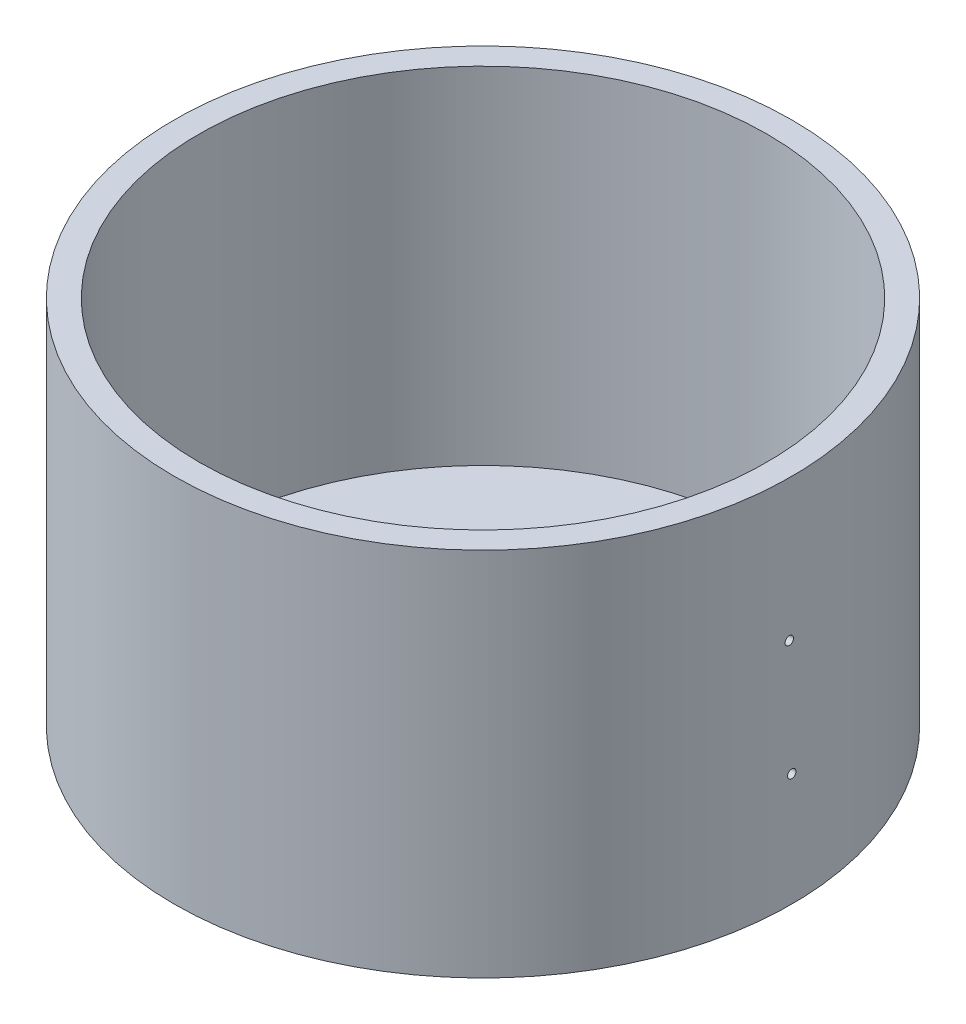
SolidWorks part; units mm, degrees
ref_plane "Front Plane" through (0, 0, 0) normal (0, 0, 1) x (1, 0, 0)
ref_plane "Top Plane" through (0, 0, 0) normal (0, 1, 0) x (1, 0, 0)
ref_plane "Right Plane" through (0, 0, 0) normal (1, 0, 0) x (0, 0, -1)
sketch "Sketch1" plane through (0, 0, 0) normal (0, 1, 0) x (1, 0, 0)
  circle A0 centre (0, 0) radius 12.5
  circle A1 centre (0, 0) radius 11.5
  dimension "D1" = 25
  dimension "D2" = 23
extrude "Boss-Extrude1" add sketch "Sketch1" along normal blind 14
sketch "Sketch2" plane through (0, 0, 0) normal (0, -1, 0) x (-1, 0, 0)
  circle A0 centre (0, 0) radius 12.5
  circle A1 centre (0, 0) radius 7.5
  dimension "D1" = 15
extrude "Boss-Extrude2" add sketch "Sketch2" along normal blind 1 contours A0 | A1
hole_wizard "#80 (0.0135) Diameter Hole1" positions "3DSketch1" profile "Sketch3" hole size "#80" standard "ANSI Inch"
sketch3d "3DSketch1"
  point P0 (12.4996, 8.2916, 0.0994)
  point P2 (12.4996, 8.2916, 0.0994)
  point P9 (0, 0, 0)
  point P10 (12.4996, 7.3056, 0.0994)
  dimension "D1" = 15
sketch "Sketch3" plane through (12.4996, 8.2916, 0.0994) normal (0, 1, 0) x (0.008, 0, -1)
  line L0 (0, 0) -> (0, 1)
  line L1 (0, 1) -> (0.1714, 1)
  line L2 (0.1714, 1) -> (0.1714, 0)
  line L5 (0.1714, 0) -> (0, 0)
  line L11 (0, -6.35) -> (0, 107.95) construction
  dimension "Thru Hole Dia." = 0.3429
  dimension "Thru Hole Depth" = 1
hole_wizard "#80 (0.0135) Diameter Hole2" positions "3DSketch3" profile "Sketch4" hole size "#80" standard "ANSI Inch"
sketch3d "3DSketch3"
  point P0 (12.5, 3.5707, 0)
  dimension "D1" = 13
sketch "Sketch4" plane through (12.5, 3.5707, 0) normal (0, 1, 0) x (0, 0, -1)
  line L0 (0, 0) -> (0, 1)
  line L1 (0, 1) -> (0.1714, 1)
  line L2 (0.1714, 1) -> (0.1714, 0)
  line L5 (0.1714, 0) -> (0, 0)
  line L11 (0, -6.35) -> (0, 107.95) construction
  dimension "Thru Hole Dia." = 0.3429
  dimension "Thru Hole Depth" = 1
